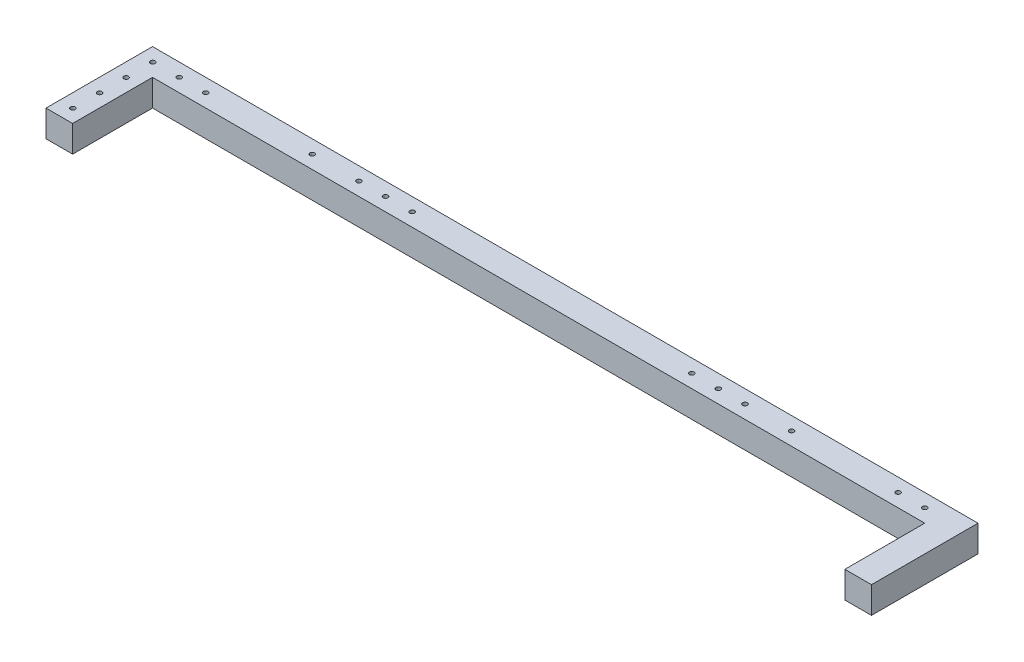
SolidWorks part; units mm, degrees
ref_plane "前视基准面" through (0, 0, 0) normal (0, 0, 1) x (1, 0, 0)
ref_plane "上视基准面" through (0, 0, 0) normal (0, 1, 0) x (1, 0, 0)
ref_plane "右视基准面" through (0, 0, 0) normal (1, 0, 0) x (0, 0, -1)
sketch "草图1" plane through (0, 0, 0) normal (0, 1, 0) x (1, 0, 0)
  line L1 (-290, -10) -> (290, -10)
  line L2 (-290, -10) -> (-290, 10)
  line L3 (-290, 10) -> (290, 10)
  line L4 (290, -10) -> (290, 10)
  line L5 (-290, -10) -> (290, 10) construction
  line L6 (-290, 10) -> (290, -10) construction
  line L7 (-290, 10) -> (-310, 10)
  line L8 (-290, 10) -> (-290, -70)
  line L9 (-290, -70) -> (-310, -70)
  line L10 (-310, 10) -> (-310, -70)
  line L11 (290, 10) -> (310, 10)
  line L12 (290, 10) -> (290, -70)
  line L13 (290, -70) -> (310, -70)
  line L14 (310, 10) -> (310, -70)
  point P0 (0, 0)
  dimension "D1" = 580
  dimension "D2" = 20
  dimension "D3" = 20
  dimension "D4" = 20
  dimension "D5" = 80
  dimension "D6" = 80
extrude "凸台-拉伸1" add sketch "草图1" along normal blind 20 contours L1 L4 L3 L2 | L7 L10 L9 L8 L2 | L14 L11 L4 L12 L13
sketch "草图2" plane through (0, 20, 0) normal (0, 1, 0) x (1, 0, 0)
  line L1 (-310, 10) -> (-290, 10)
  line L2 (-310, 10) -> (-310, -70)
  line L3 (-310, -70) -> (-290, -70)
  line L4 (-290, 10) -> (-290, -70)
  circle A0 centre (-299.7857, 0) radius 1.75
  circle A1 centre (-299.7857, -20) radius 1.75
  circle A2 centre (-299.7857, -40) radius 1.75
  circle A3 centre (-299.7857, -60) radius 1.75
  dimension "D1" = 3.5
  dimension "D2" = 10
  dimension "D3" = 10
  dimension "D4" = 20
  dimension "D5" = 20
sketch "草图3" plane through (0, 0, 0) normal (0, -1, 0) x (1, 0, 0)
  line L0 (-310, -10) -> (310, -10) construction
  line L1 (-290, 10) -> (290, 10)
  line L2 (-290, 10) -> (-290, -10)
  line L3 (-290, -10) -> (290, -10)
  line L4 (290, 10) -> (290, -10)
  line L5 (290, 70) -> (290, 10) construction
  line L6 (0, 0) -> (0, 50.5915) construction
  circle A0 centre (-280, 0) radius 1.75
  circle A1 centre (-260, 0) radius 1.75
  circle A2 centre (-180, 0) radius 1.75
  circle A3 centre (180, 0) radius 1.75
  circle A4 centre (260, 0) radius 1.75
  circle A5 centre (280, 0) radius 1.75
  dimension "D1" = 10
  dimension "D5" = 3.5
  dimension "D2" = 10
  dimension "D3" = 20
  dimension "D4" = 80
sketch "草图4" plane through (0, 20, 0) normal (0, 1, 0) x (1, 0, 0)
  line L0 (0, 0) -> (0, -29.5634) construction
  circle A0 centre (-125, 0) radius 1.75
  circle A1 centre (-105, 0) radius 1.75
  circle A2 centre (-145, 0) radius 1.75
  circle A3 centre (105, 0) radius 1.75
  circle A4 centre (125, 0) radius 1.75
  circle A5 centre (145, 0) radius 1.75
  dimension "D1" = 250
  dimension "D6" = 3.5
  dimension "D2" = 20
  dimension "D3" = 20
  dimension "D4" = 20
  dimension "D5" = 20
extrude "切除-拉伸1" cut sketch "草图2" against normal up to next contours A2 | A3 | A1 | A0
extrude "切除-拉伸2" cut sketch "草图4" against normal up to next
extrude "切除-拉伸3" cut sketch "草图3" against normal up to next contours A3 | A5 | A4 | A0 | A1 | A2
sketch "草图5" plane through (0, 20, 0) normal (0, 1, 0) x (1, 0, 0)
  line L0 (-310, 10) -> (310, 10) construction
  line L1 (-290, -10) -> (290, -10)
  line L2 (-290, -10) -> (-290, 10)
  line L3 (-290, 10) -> (290, 10)
  line L4 (290, -10) -> (290, 10)
  line L5 (290, -70) -> (290, -10) construction
  line L7 (-310, 10) -> (310, 10)
  line L8 (-310, 10) -> (-310, -70)
  line L9 (-310, -70) -> (310, -70)
  line L10 (310, 10) -> (310, -70)
